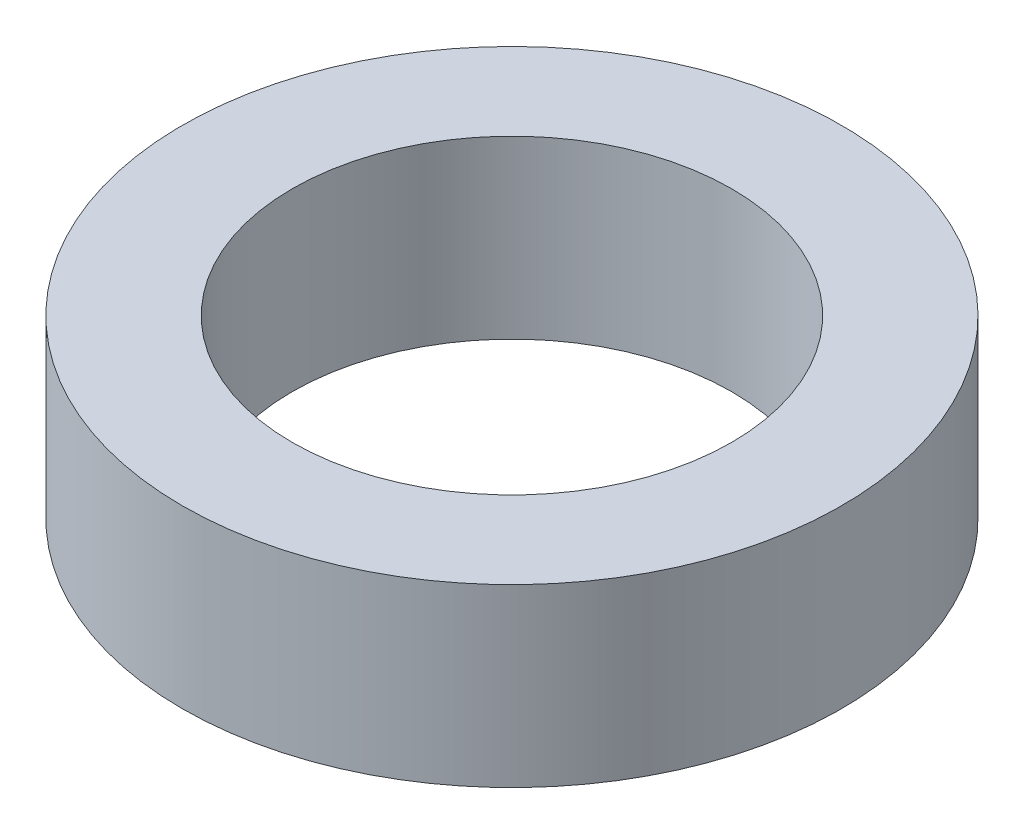
SolidWorks part; units mm, degrees
ref_plane "Front Plane" through (0, 0, 0) normal (0, 0, 1) x (1, 0, 0)
ref_plane "Top Plane" through (0, 0, 0) normal (0, 1, 0) x (1, 0, 0)
ref_plane "Right Plane" through (0, 0, 0) normal (1, 0, 0) x (0, 0, -1)
sketch "Sketch1" plane through (0, 0, 0) normal (0, 1, 0) x (1, 0, 0)
  circle A0 centre (0, 0) radius 2.5
  circle A1 centre (0, 0) radius 5
  dimension "D1" = 10
  dimension "D2" = 5
extrude "Boss-Extrude1" [suppressed] add sketch "Sketch1" along normal blind 4
sketch "Sketch2" [suppressed] plane through (0, 0, 0) normal (0, 1, 0) x (1, 0, 0)
  circle A0 centre (0, 0) radius 7.5
  circle A1 centre (0, 0) radius 14
  dimension "D1" = 15
  dimension "D2" = 28
extrude "Boss-Extrude2" [suppressed] add sketch "Sketch2" along normal blind 8
sketch "Sketch3" [suppressed] plane through (0, 0, 0) normal (0, 1, 0) x (1, 0, 0)
  circle A0 centre (0, 0) radius 25
  circle A1 centre (0, 0) radius 32.5
  dimension "D1" = 65
  dimension "D2" = 50
extrude "Boss-Extrude3" [suppressed] add sketch "Sketch3" along normal blind 7
sketch "Sketch4" plane through (0, 0, 0) normal (0, 1, 0) x (1, 0, 0)
  circle A0 centre (0, 0) radius 5
  circle A1 centre (0, 0) radius 7.5
  dimension "D1" = 10
  dimension "D2" = 15
extrude "Boss-Extrude4" add sketch "Sketch4" along normal blind 4
